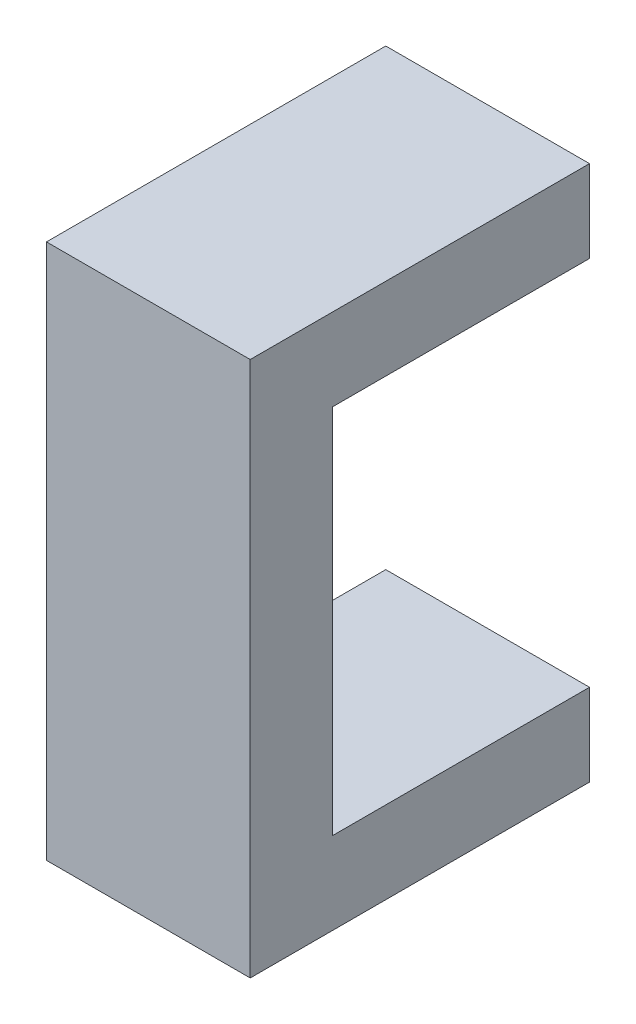
SolidWorks part; units mm, degrees
ref_plane "Front Plane" through (0, 0, 0) normal (0, 0, 1) x (1, 0, 0)
ref_plane "Top Plane" through (0, 0, 0) normal (0, 1, 0) x (1, 0, 0)
ref_plane "Right Plane" through (0, 0, 0) normal (1, 0, 0) x (0, 0, -1)
sketch "Sketch1" plane through (0, 0, 0) normal (1, 0, 0) x (0, 0, -1)
  line L1 (2.5, 16.3) -> (-2.5, 16.3)
  line L2 (2.5, 16.3) -> (2.5, -16.3)
  line L3 (2.5, -16.3) -> (-2.5, -16.3)
  line L4 (-2.5, 16.3) -> (-2.5, -16.3)
  line L5 (2.5, 16.3) -> (-2.5, -16.3) construction
  line L6 (2.5, -16.3) -> (-2.5, 16.3) construction
  line L7 (2.5, 16.3) -> (18.15, 16.3)
  line L8 (2.5, 16.3) -> (2.5, 11.3)
  line L9 (2.5, 11.3) -> (18.15, 11.3)
  line L10 (18.15, 16.3) -> (18.15, 11.3)
  line L11 (2.5, -16.3) -> (18.15, -16.3)
  line L12 (2.5, -16.3) -> (2.5, -11.3)
  line L13 (2.5, -11.3) -> (18.15, -11.3)
  line L14 (18.15, -16.3) -> (18.15, -11.3)
  point P0 (0, 0)
  dimension "D1" = 32.6
  dimension "D2" = 5
  dimension "D3" = 5
  dimension "D4" = 15.65
  dimension "D5" = 15.65
  dimension "D6" = 5
extrude "Boss-Extrude1" add sketch "Sketch1" along normal blind 12.4 contours L10 L7 L2 L9 | L1 L4 L3 L2 | L11 L14 L13 L2
